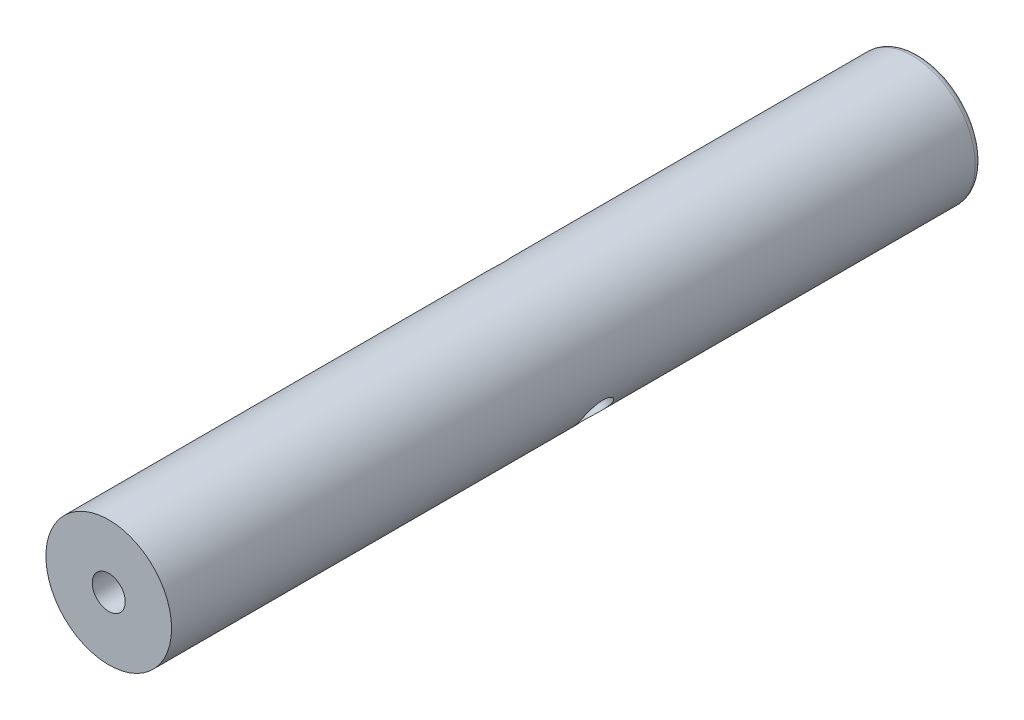
SolidWorks part; units mm, degrees
ref_plane "Plano frontal" through (0, 0, 0) normal (0, 0, 1) x (1, 0, 0)
ref_plane "Plano superior" through (0, 0, 0) normal (0, 1, 0) x (1, 0, 0)
ref_plane "Plano direito" through (0, 0, 0) normal (1, 0, 0) x (0, 0, -1)
sketch "Esboço1" plane through (0, 0, 0) normal (0, 0, 1) x (1, 0, 0)
  circle A0 centre (240.7084, 2.5961) radius 4.7625
  dimension "D1" = 9.525
extrude "Ressalto-extrusão1" add sketch "Esboço1" along normal blind 61.4
hole_wizard "Furo roscado de M5x0.81" positions "Esboço5" profile "Esboço4" tap size "M5x0.8" standard "Métrico Ansi"
sketch "Esboço5" plane through (0, 0, 0) normal (0, 0, -1) x (-1, 0, 0)
  point P0 (-240.7084, 2.5961)
sketch "Esboço4" plane through (240.7084, 2.5961, 0) normal (1, 0, 0) x (0, 1, 0)
  line L0 (0, 0) -> (0, 15.2618)
  line L1 (0, 15.2618) -> (2.1, 14)
  line L2 (2.1, 14) -> (2.1, 0)
  line L5 (2.1, 0) -> (0, 0)
  line L10 (0, 15.2618) -> (-2.1, 14) construction
  line L11 (0, -6.35) -> (0, 107.95) construction
  dimension "Tap Drill Dia." = 4.2
  dimension "Tap Drill Depth" = 14
  dimension "Drill Angle" = 118
cosmetic thread "Rosca de furo2" parameters "D1"=10, "D2"=5
cosmetic thread "Representação de rosca3" parameters "D1"=5, "D2"=5
fillet "Filete1" radius 0.5 1 edges at (245.4709, 2.5961, 0)
hole_wizard "Broca de rosquear para tarraxa de M3x0.51" positions "Esboço7" profile "Esboço6" hole size "M3x0.5" standard "Métrico Ansi"
sketch "Esboço7" plane through (0, 0, 61.4) normal (0, 0, 1) x (1, 0, 0)
  circle A0 centre (240.7084, 2.5961) radius 4.7625 construction
  point P0 (240.7084, 2.5961)
  dimension "D1" = 0
sketch "Esboço6" plane through (240.7084, 2.5961, 61.4) normal (1, 0, 0) x (0, -1, 0)
  line L0 (0, 0) -> (0, 5.7511)
  line L1 (0, 5.7511) -> (1.25, 5)
  line L2 (1.25, 5) -> (1.25, 0)
  line L5 (1.25, 0) -> (0, 0)
  line L10 (0, 5.7511) -> (-1.25, 5) construction
  line L11 (0, -6.35) -> (0, 107.95) construction
  dimension "Hole Dia." = 2.5
  dimension "Hole Depth" = 5
  dimension "Drill Angle" = 118
hole_wizard "Broca de rosquear para tarraxa de M3x0.52" positions "3DSketch1" profile "Esboço8" hole size "M3x0.5" standard "Métrico Ansi"
sketch3d "3DSketch1"
  point P0 (236.8194, 5.3451, 28.4319)
sketch "Esboço8" plane through (236.8194, 5.3451, 28.4319) normal (0, 0, 1) x (-0.5772, -0.8166, 0)
  line L0 (0, 0) -> (0, 10.7511)
  line L1 (0, 10.7511) -> (1.25, 10)
  line L2 (1.25, 10) -> (1.25, 0)
  line L5 (1.25, 0) -> (0, 0)
  line L10 (0, 10.7511) -> (-1.25, 10) construction
  line L11 (0, -6.35) -> (0, 107.95) construction
  dimension "Hole Dia." = 2.5
  dimension "Hole Depth" = 10
  dimension "Drill Angle" = 118
cosmetic thread "Representação de rosca2" parameters "D2"=3
equation "\"D1@Esboço1\"=\"D_Barra@Inversor3.SLDASM\""
